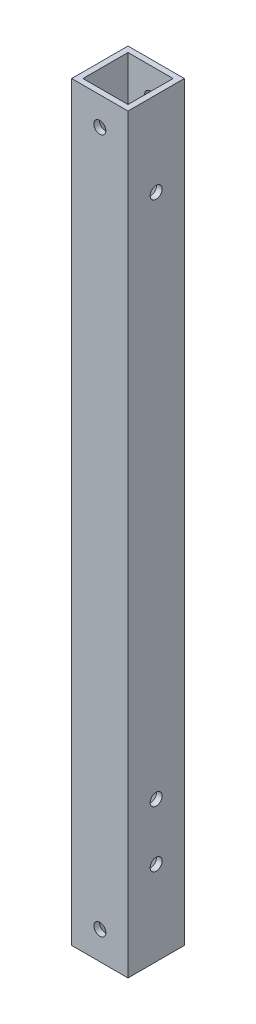
SolidWorks part; units mm, degrees
ref_plane "Front" through (0, 0, 0) normal (0, 0, 1) x (1, 0, 0)
ref_plane "Top" through (0, 0, 0) normal (0, 1, 0) x (1, 0, 0)
ref_plane "Right" through (0, 0, 0) normal (1, 0, 0) x (0, 0, -1)
sketch "ｽｹｯﾁ1" plane through (0, 0, 0) normal (0, 1, 0) x (1, 0, 0)
  line L0 (-6, 6) -> (6, 6)
  line L1 (-7.5, 7.5) -> (7.5, 7.5)
  line L2 (-7.5, 7.5) -> (-7.5, -7.5)
  line L3 (-7.5, -7.5) -> (7.5, -7.5)
  line L4 (7.5, 7.5) -> (7.5, -7.5)
  line L5 (0, -7.5) -> (0, 7.5) construction
  line L6 (-7.5, 0) -> (7.5, 0) construction
  line L7 (6, 6) -> (6, -6)
  line L8 (-6, -6) -> (6, -6)
  line L9 (-6, 6) -> (-6, -6)
  point P0 (0, 0)
  dimension "D1" = 15
  dimension "D2" = 15
  dimension "D3" = 1.5
extrude "ﾎﾞｽ - 押し出し1" add sketch "ｽｹｯﾁ1" along normal blind 200
sketch "ｽｹｯﾁ2" plane through (0, 0, 7.5) normal (0, 0, 1) x (1, 0, 0)
  line L0 (7.5, 200) -> (7.5, 0) construction
  line L1 (-7.5, 200) -> (7.5, 200) construction
  line L2 (-7.5, 0) -> (7.5, 0) construction
  circle A0 centre (0, 192.5) radius 1.6
  circle A1 centre (0, 7.5) radius 1.6
  dimension "D1" = 7.5
  dimension "D2" = 7.5
  dimension "D3" = 3.2
  dimension "D4" = 3.2
  dimension "D5" = 7.5
  dimension "D6" = 7.5
extrude "ｶｯﾄ - 押し出し1" cut sketch "ｽｹｯﾁ2" against normal through all
sketch "ｽｹｯﾁ3" plane through (7.5, 0, 0) normal (1, 0, 0) x (0, 0, -1)
  line L0 (-7.5, 0) -> (7.5, 0) construction
  line L1 (7.5, 200) -> (7.5, 0) construction
  line L2 (-7.5, 200) -> (7.5, 200) construction
  line L3 (-7.5, 200) -> (-7.5, 0) construction
  circle A0 centre (0, 177.5) radius 1.6
  circle A1 centre (0, 22.5) radius 1.6
  circle A2 centre (0, 37.5) radius 1.6
  dimension "D1" = 3.2
  dimension "D2" = 3.2
  dimension "D3" = 22.5
  dimension "D4" = 7.5
  dimension "D5" = 7.5
  dimension "D6" = 22.5
  dimension "D7" = 3.2
  dimension "D8" = 7.5
  dimension "D9" = 15
extrude "ｶｯﾄ - 押し出し2" cut sketch "ｽｹｯﾁ3" against normal through all
